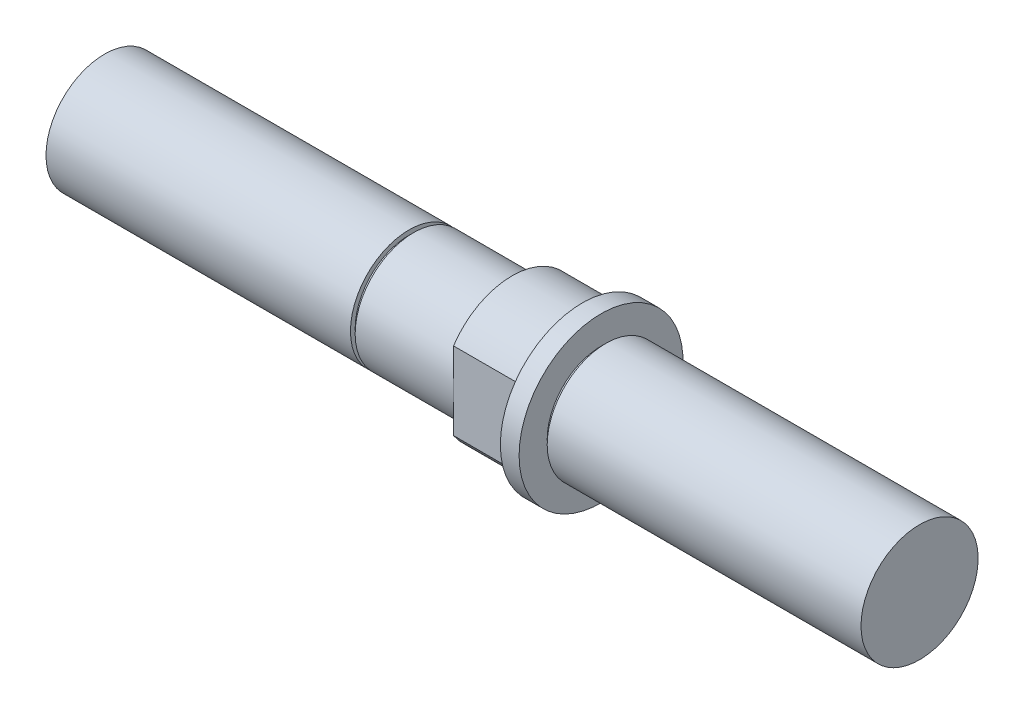
SolidWorks part; units mm, degrees
material "Alloy Steel"
ref_plane "Front Plane" through (0, 0, 0) normal (0, 0, 1) x (1, 0, 0)
ref_plane "Top Plane" through (0, 0, 0) normal (0, 1, 0) x (1, 0, 0)
ref_plane "Right Plane" through (0, 0, 0) normal (1, 0, 0) x (0, 0, -1)
sketch "Sketch2" plane through (0, 0, 0) normal (0, 0, 1) x (1, 0, 0)
  line L0 (0, 0) -> (0, 12.5)
  line L1 (0, 12.5) -> (-68, 12.5)
  line L2 (-68, 12.5) -> (-68, 17.5)
  line L3 (-68, 17.5) -> (-72, 17.5)
  line L4 (-72, 17.5) -> (-72, 15)
  line L5 (-72, 15) -> (-87, 15)
  line L6 (-87, 15) -> (-87, 12.5)
  line L7 (-87, 12.5) -> (-174, 12.5)
  line L8 (-174, 12.5) -> (-174, 0)
  line L9 (-174, 0) -> (0, 0) construction
  line L10 (0, 0) -> (-174, 0)
  dimension "D1" = 25
  dimension "D2" = 35
  dimension "D3" = 30
  dimension "D4" = 25
  dimension "D5" = 87
  dimension "D6" = 4
  dimension "D7" = 15
  dimension "D8" = 68
revolve "Revolve1" add sketch "Sketch2" angle 360 about L9
sketch "Sketch3" plane through (0, 0, 0) normal (0, 0, 1) x (1, 0, 0)
  line L0 (-68, 12.5) -> (-67, 12.5)
  line L1 (0, 12.5) -> (-68, 12.5) construction
  line L2 (-67, 12.5) -> (-67, 11.5)
  line L3 (-67, 11.5) -> (-68, 11.5)
  line L4 (-68, -17.5) -> (-68, 17.5) construction
  line L5 (-68, 11.5) -> (-68, 12.5)
  line L6 (-174, 0) -> (0, 0) construction
  line L7 (-174, 12.5) -> (-174, -12.5) construction
  line L8 (-87, 12.5) -> (-174, 12.5) construction
  line L9 (-109, 12.5) -> (-108, 12.5)
  line L10 (-109, 12.5) -> (-109, 11.5)
  line L11 (-109, 11.5) -> (-108, 11.5)
  line L12 (-108, 12.5) -> (-108, 11.5)
  point P20 (-108.5, 11.5)
  dimension "D1" = 1
  dimension "D2" = 1
  dimension "D3" = 23
  dimension "D4" = 23
  dimension "D5" = 65
revolve "Cut-Revolve1" cut sketch "Sketch3" angle 360 about L6
sketch "Sketch4" plane through (-87, 0, 0) normal (-1, 0, 0) x (0, 0, 1)
  line L0 (0, 0) -> (0, -12.5) construction
  line L1 (-12.5, 8.2916) -> (-12.5, -8.2916)
  line L2 (12.5, 8.2916) -> (12.5, -8.2916)
  circle A0 centre (0, 0) radius 12.5 construction
  circle A1 centre (0, 0) radius 12.5 construction
  circle A2 centre (0, 0) radius 15
  circle M6 centre (0, 0) radius 15
  dimension "D1" = 30
  dimension "D2" = 25
extrude "Cut-Extrude2" cut sketch "Sketch4" against normal up to surface (15 mm away) contours L2 M6 | L1 M6 up to face at (-72, 0, 15)
